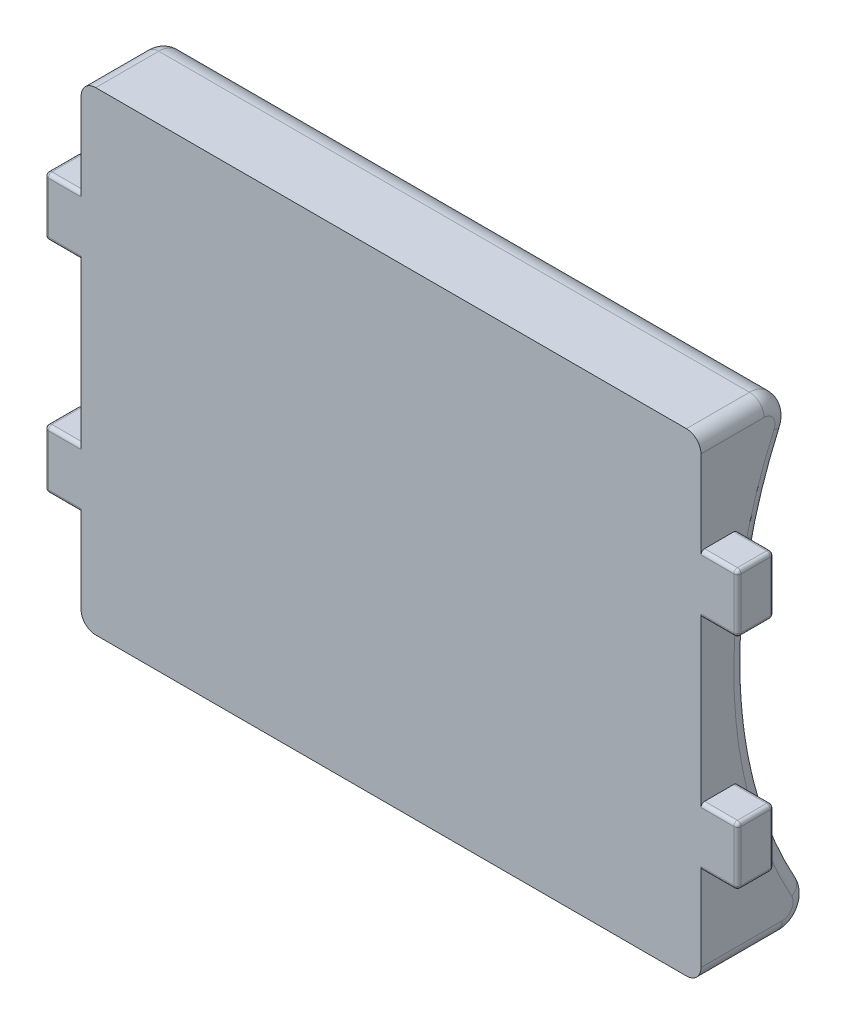
SolidWorks part; units mm, degrees
ref_plane "Alzado" through (0, 0, 0) normal (0, 0, 1) x (1, 0, 0)
ref_plane "Planta" through (0, 0, 0) normal (0, 1, 0) x (1, 0, 0)
ref_plane "Vista lateral" through (0, 0, 0) normal (1, 0, 0) x (0, 0, -1)
sketch "Croquis1" plane through (0, 0, 0) normal (0, 0, 1) x (1, 0, 0)
  line L1 (42.5, -32.5) -> (-42.5, -32.5)
  line L2 (42.5, -32.5) -> (42.5, 32.5)
  line L3 (42.5, 32.5) -> (-42.5, 32.5)
  line L4 (-42.5, -32.5) -> (-42.5, 32.5)
  line L5 (42.5, -32.5) -> (-42.5, 32.5) construction
  line L6 (42.5, 32.5) -> (-42.5, -32.5) construction
  point P0 (0, 0)
  dimension "D1" = 85
  dimension "D2" = 65
extrude "Saliente-Extruir1" add sketch "Croquis1" along normal blind 5
sketch "Croquis3" plane through (42.5, 0, 0) normal (1, 0, 0) x (0, 0, -1)
  line L0 (-5, -32.5) -> (-5, 32.5) construction
  line L1 (-5, 19) -> (0, 19)
  line L2 (-5, 19) -> (-5, 11)
  line L3 (-5, 11) -> (0, 11)
  line L4 (0, 19) -> (0, 11)
  line L5 (0, -32.5) -> (0, 32.5) construction
  line L6 (0, 0) -> (-15.3496, 0) construction
  line L7 (0, -19) -> (0, -11)
  line L8 (-5, -11) -> (0, -11)
  line L9 (-5, -19) -> (-5, -11)
  line L10 (-5, -19) -> (0, -19)
  point P8 (0, 15)
  point P9 (0, 0)
  dimension "D1" = 8
  dimension "D2" = 15
extrude "Saliente-Extruir3" add sketch "Croquis3" along normal blind 5
mirror "Simetría1" about plane through (0, 0, 0) normal (1, 0, 0) of "Saliente-Extruir3"
sketch "Croquis2" plane through (42.5, 0, 0) normal (1, 0, 0) x (0, 0, -1)
  line L0 (0, 32.5) -> (9.3134, 32.5)
  line L1 (0, -32.5) -> (12.4307, -32.5)
  line L2 (3, 32.5) -> (3, 2.5) construction
  line L3 (0, -32.5) -> (0, -19) construction
  line L4 (0, 32.5) -> (0, -32.5)
  arc A0 (9.3134, 32.5) -> (12.4307, -32.5) centre (63, 2.5) ccw
  circle A1 centre (63, 2.5) radius 60 construction
  dimension "D1" = 123
  dimension "D2" = 30
  dimension "D4" = 120
  dimension "D3" = 3
extrude "Saliente-Extruir2" add sketch "Croquis2" against normal up to surface (85 mm away) up to face at (-42.5, -25.75, 2.5)
fillet "Redondeo1" radius 3.5 2 edges at (0, -32.5, -12.4307) (0, 32.5, -9.3134)
fillet "Redondeo2" radius 2 10 edges at (-42.5, 32.5, 0.6764) (-42.5, 30.9047, -6.5836) (-42.5, -32.5, -0.5714) (-42.5, -30.7767, -9.1582) (42.5, -32.5, -0.5714) (42.5, -30.7767, -9.1582) (42.5, 32.5, 0.6764) (42.5, 30.9047, -6.5836) (42.5, -0.1436, -1.5568) (-42.5, -0.1436, -1.5568)
fillet "Redondeo3" radius 0.5 32 edges at (45, 19, 5) (45, 11, 5) (45, 11, 0) (45, 19, 0) (47.5, 15, 5) (47.5, 11, 2.5) (47.5, 15, 0) (47.5, 19, 2.5) (45, -19, 5) (45, -19, 0) (45, -11, 0) (45, -11, 5) (47.5, -19, 2.5) (47.5, -15, 0) (47.5, -11, 2.5) (47.5, -15, 5) (-47.5, 15, 5) (-45, 11, 5) (-47.5, 19, 2.5) (-45, 19, 5) (-47.5, 15, 0) (-45, 19, 0) (-47.5, 11, 2.5) (-45, 11, 0) (-47.5, -19, 2.5) (-45, -19, 0) (-47.5, -15, 5) (-45, -19, 5) (-47.5, -11, 2.5) (-45, -11, 5) (-47.5, -15, 0) (-45, -11, 0)
